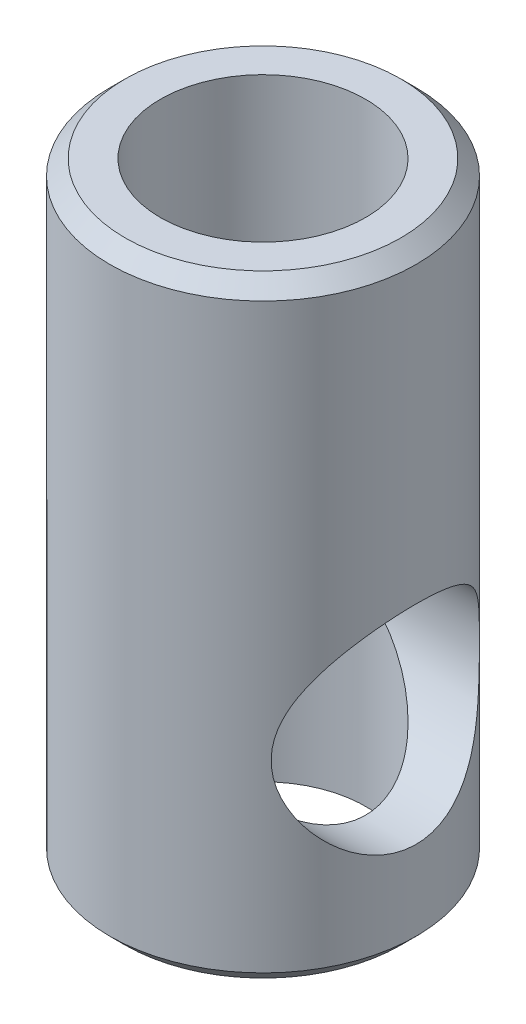
SolidWorks part; units mm, degrees
ref_plane "前视基准面" through (0, 0, 0) normal (0, 0, 1) x (1, 0, 0)
ref_plane "上视基准面" through (0, 0, 0) normal (0, 1, 0) x (1, 0, 0)
ref_plane "右视基准面" through (0, 0, 0) normal (1, 0, 0) x (0, 0, -1)
sketch "草图1" plane through (0, 0, 0) normal (0, 0, 1) x (1, 0, 0)
  line B0 (0, 0) -> (5, 0)
  line B1 (5, 0) -> (5, 20)
  line B2 (5, 20) -> (0, 20)
  line B3 (0, 20) -> (0, 0)
sketch_block_instance "A$C132D5969-1"
sketch_block "A$C132D5969"
revolve "旋转1" add sketch "草图1" angle 360 about L3
sketch "草图3" plane through (0, 20, 0) normal (0, 1, 0) x (1, 0, 0)
  circle A0 centre (0, 0) radius 3.35
extrude "切除-拉伸1" cut sketch "草图3" against normal through all
sketch "草图4" plane through (0, 0, 0) normal (1, 0, 0) x (0, 0, -1)
  line L0 (-5, 0) -> (5, 0) construction
  circle A0 centre (0, 6.5) radius 3.4
  dimension "D1" = 6.5
extrude "切除-拉伸2" cut sketch "草图4" against normal through all and the other way through all
chamfer "倒角1" distance 0.5 angle 45 2 edges at (0, 20, 5) (0, 0, 5)
